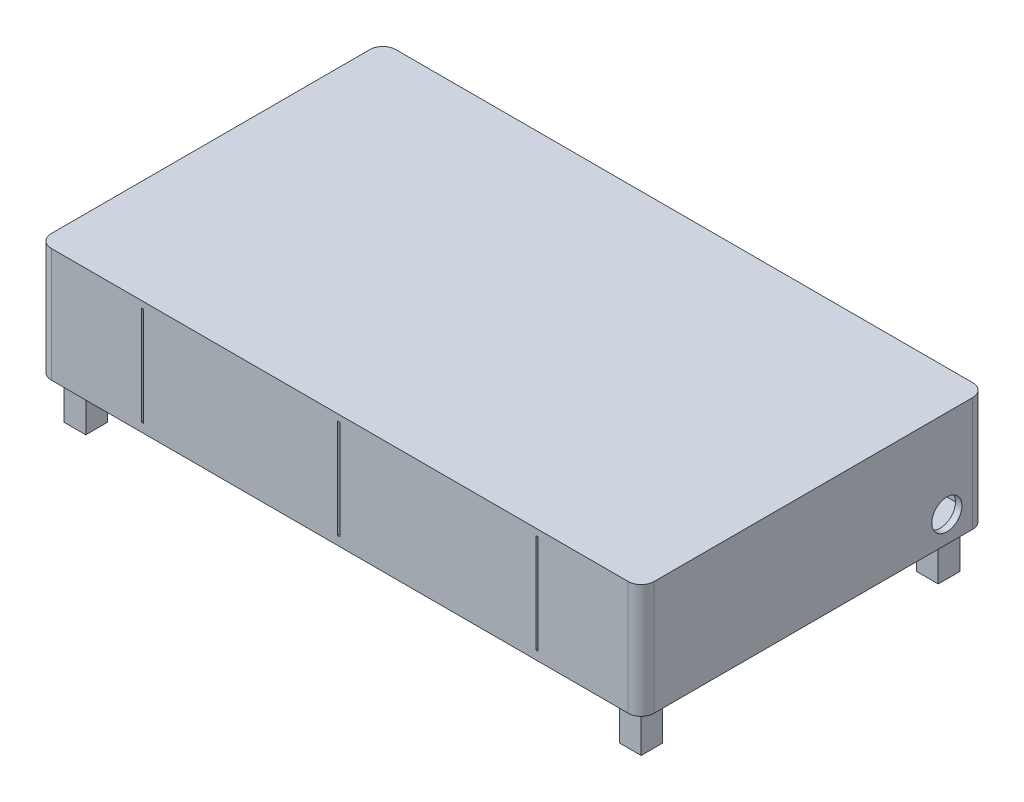
SolidWorks part; units mm, degrees
ref_plane "Front Plane" through (0, 0, 0) normal (0, 0, 1) x (1, 0, 0)
ref_plane "Top Plane" through (0, 0, 0) normal (0, 1, 0) x (1, 0, 0)
ref_plane "Right Plane" through (0, 0, 0) normal (1, 0, 0) x (0, 0, -1)
sketch "Sketch1" plane through (0, 0, 0) normal (0, 1, 0) x (1, 0, 0)
  line L0 (68.5, -18) -> (68.5, 17)
  line L1 (-70, 40) -> (70, 40)
  line L2 (-70, 40) -> (-70, -40)
  line L3 (-70, -40) -> (70, -40)
  line L4 (70, 40) -> (70, -40)
  line L5 (-70, 40) -> (70, -40) construction
  line L6 (-70, -40) -> (70, 40) construction
  line L7 (68.5, 17) -> (30, 17)
  line L8 (30, 17) -> (30, 38.5)
  line L9 (30, 38.5) -> (-58.5, 38.5)
  line L10 (-68.5, 28.5) -> (-68.5, -28.5)
  line L12 (-40, -38.5) -> (-40, -18)
  line L13 (-40, -18) -> (68.5, -18)
  line L14 (-68.5, 28.5) -> (-58.5, 28.5)
  line L15 (-58.5, 28.5) -> (-58.5, 38.5)
  line L16 (-68.5, -28.5) -> (-58.5, -28.5)
  line L17 (-58.5, -28.5) -> (-58.5, -38.5)
  line L18 (-58.5, -38.5) -> (-40, -38.5)
  point P0 (0, 0)
  dimension "D1" = 140
  dimension "D2" = 80
  dimension "D3" = 1.5
  dimension "D4" = 1.5
  dimension "D6" = 22
  dimension "D7" = 110
  dimension "D8" = 23
  dimension "D9" = 40
  dimension "D10" = 1.5
  dimension "D11" = 10
  dimension "D12" = 10
  dimension "D13" = 10
  dimension "D14" = 10
extrude "Boss-Extrude1" add sketch "Sketch1" along normal blind 2
sketch "Sketch2" plane through (0, 2, 0) normal (0, 1, 0) x (1, 0, 0)
  line L0 (-45.5947, 40) -> (-45.5947, 38.5)
  line L1 (-45.5947, -38.5) -> (-45.5947, -40)
  line L2 (0, 40) -> (0, -40) construction
  line L3 (-46.0947, 40) -> (-46.0947, 38.5)
  line L4 (-46.0947, -38.5) -> (-46.0947, -40)
  line L5 (45.5947, -38.5) -> (45.5947, -40)
  line L6 (46.0947, -38.5) -> (46.0947, -40)
  line L7 (45.5947, 40) -> (45.5947, 38.5)
  line L8 (68.5, -38.5) -> (68.5, 38.5)
  line L9 (68.5, 38.5) -> (-68.5, 38.5)
  line L10 (-68.5, 38.5) -> (-68.5, -38.5)
  line L11 (-68.5, -38.5) -> (68.5, -38.5)
  line L12 (68.5, -38.5) -> (68.5, 38.5)
  line L13 (68.5, 38.5) -> (46.0947, 38.5)
  line L14 (-68.5, 38.5) -> (-68.5, -38.5)
  line L15 (-68.5, -38.5) -> (-46.0947, -38.5)
  line L16 (70, -40) -> (70, 40)
  line L17 (70, 40) -> (-70, 40)
  line L18 (-70, 40) -> (-70, -40)
  line L19 (-70, -40) -> (70, -40)
  line L20 (70, -40) -> (70, 40)
  line L21 (70, 40) -> (46.0947, 40)
  line L22 (-70, 40) -> (-70, -40)
  line L23 (-70, -40) -> (-46.0947, -40)
  line L24 (46.0947, 40) -> (46.0947, 38.5)
  line L25 (0, 40) -> (0, 38.5)
  line L26 (0, -38.5) -> (0, -40)
  line L27 (-0.5, -38.5) -> (-0.5, -40)
  line L28 (-0.5, 40) -> (-0.5, 38.5)
  line L29 (-46.0947, 38.5) -> (-68.5, 38.5)
  line L30 (-46.0947, 40) -> (-70, 40)
  line L31 (-0.5, 40) -> (-45.5947, 40)
  line L32 (-0.5, 38.5) -> (-45.5947, 38.5)
  line L33 (45.5947, 40) -> (0, 40)
  line L34 (45.5947, 38.5) -> (0, 38.5)
  line L35 (46.0947, -38.5) -> (68.5, -38.5)
  line L36 (46.0947, -40) -> (70, -40)
  line L37 (0, -38.5) -> (45.5947, -38.5)
  line L38 (0, -40) -> (45.5947, -40)
  line L39 (-45.5947, -38.5) -> (-0.5, -38.5)
  line L40 (-45.5947, -40) -> (-0.5, -40)
  dimension "D1" = 1.5
  dimension "D2" = 0
  dimension "D3" = 0.5
  dimension "D4" = 0.5
extrude "Boss-Extrude3" add sketch "Sketch2" along normal blind 23
sketch "Sketch3" plane through (0, 25, 0) normal (0, 1, 0) x (1, 0, 0)
  line L5 (-70, 40) -> (70, 40)
  line L6 (-70, 40) -> (-70, -40)
  line L7 (-70, -40) -> (70, -40)
  line L16 (70, 40) -> (70, -40)
extrude "Boss-Extrude4" add sketch "Sketch3" along normal blind 1.5
sketch "Sketch4" plane through (70, 0, 0) normal (1, 0, 0) x (0, 0, -1)
  line L0 (-40, 6) -> (40, 6) construction
  line L1 (-40, 26.5) -> (-40, 0) construction
  line L2 (40, 26.5) -> (40, 0) construction
  line L3 (-40, 0) -> (40, 0) construction
  circle A0 centre (31, 6) radius 3.5
  dimension "D1" = 7
  dimension "D2" = 9
  dimension "D3" = 6
extrude "Cut-Extrude1" cut sketch "Sketch4" against normal blind 5
fillet "Fillet1" radius 3 6 edges at (-70, 13.25, 40) (-70, 13.25, -40) (70, 13.25, -40) (70, 13.25, 40) (-68.5, 13.5, -38.5) (-68.5, 13.5, 38.5)
sketch "Sketch5" plane through (0, 0, 0) normal (0, -1, 0) x (1, 0, 0)
  line L0 (-67, 40) -> (67, 40) construction
  line L1 (-67, 37) -> (-62, 37)
  line L2 (-67, 37) -> (-67, 32)
  line L3 (-67, 32) -> (-62, 32)
  line L4 (-62, 37) -> (-62, 32)
  line L5 (-67, 37) -> (-62, 32) construction
  line L6 (-67, 32) -> (-62, 37) construction
  line L7 (-70, -37) -> (-70, 37) construction
  line L8 (-70, 0) -> (70, 0) construction
  line L9 (70, 37) -> (70, -37) construction
  line L10 (0, 40) -> (0, -40) construction
  line L11 (67, -40) -> (-67, -40) construction
  line L12 (62, 37) -> (62, 32)
  line L13 (67, 32) -> (62, 32)
  line L14 (67, 37) -> (67, 32)
  line L15 (67, 37) -> (62, 37)
  line L16 (67, -32) -> (62, -32)
  line L17 (67, -37) -> (67, -32)
  line L18 (67, -37) -> (62, -37)
  line L19 (62, -37) -> (62, -32)
  line L20 (-67, -32) -> (-62, -32)
  line L21 (-62, -37) -> (-62, -32)
  line L22 (-67, -37) -> (-62, -37)
  line L23 (-67, -37) -> (-67, -32)
  point P0 (-64.5, 34.5)
  dimension "D1" = 5
  dimension "D2" = 5
  dimension "D3" = 3
  dimension "D4" = 3
extrude "Boss-Extrude5" add sketch "Sketch5" along normal blind 10
